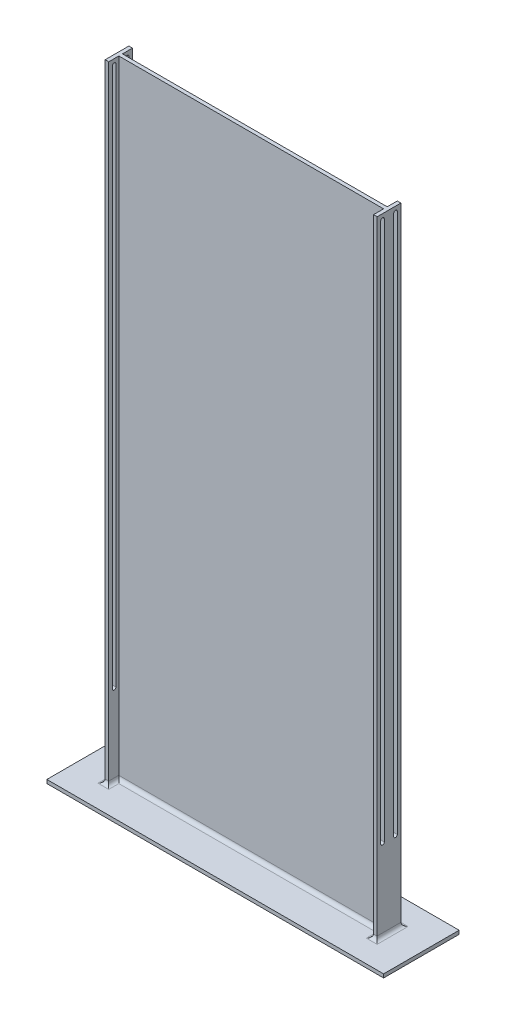
SolidWorks part; units mm, degrees
material "AISI 4340 Steel, annealed"
ref_plane "Front Plane" through (0, 0, 0) normal (0, 0, 1) x (1, 0, 0)
ref_plane "Top Plane" through (0, 0, 0) normal (0, 1, 0) x (1, 0, 0)
ref_plane "Right Plane" through (0, 0, 0) normal (1, 0, 0) x (0, 0, -1)
sketch "Sketch1" plane through (0, 0, 0) normal (1, 0, 0) x (0, 0, -1)
  line L0 (0, 0) -> (-100, 0)
  line L1 (-100, 0) -> (-100, -10)
  line L2 (-100, -10) -> (10, -10)
  line L3 (10, 0) -> (10, 1741.5)
  line L4 (10, 1741.5) -> (0, 1741.5)
  line L5 (0, 1741.5) -> (0, 0)
  line L6 (10, -10) -> (110, -10)
  line L7 (110, -10) -> (110, 0)
  line L8 (110, 0) -> (10, 0)
  dimension "D1" = 1751.5
  dimension "D2" = 10
  dimension "D3" = 10
  dimension "D4" = 100
extrude "Wall extrude" add sketch "Sketch1" along normal mid plane 736
sketch "Sketch2" plane through (368, 0, 0) normal (1, 0, 0) x (0, 0, -1)
  line L0 (5, 1741.5) -> (5, -10) construction
  line L1 (10, 1741.5) -> (0, 1741.5) construction
  line L2 (10, 0) -> (10, 1741.5) construction
  line L3 (-100, -10) -> (110, -10) construction
  line L4 (0, 1741.5) -> (38, 1741.5)
  line L6 (0, -10) -> (38, -10)
  line L7 (38, 1741.5) -> (38, -10)
  line L8 (18, 226.5) -> (18, 1726.5)
  line L9 (28, 1726.5) -> (28, 226.5)
  line L10 (-18, 1726.5) -> (-18, 226.5)
  line L11 (-8, 226.5) -> (-8, 1726.5)
  line L12 (0, 1741.5) -> (-28, 1741.5)
  line L13 (-28, 1741.5) -> (-28, -10)
  line L14 (-28, -10) -> (0, -10)
  line L15 (0, 1741.5) -> (0, 0) construction
  arc A0 (28, 1726.5) -> (18, 1726.5) centre (23, 1726.5) ccw
  arc A1 (18, 226.5) -> (28, 226.5) centre (23, 226.5) ccw
  arc A2 (-8, 226.5) -> (-18, 226.5) centre (-13, 226.5) cw
  arc A3 (-18, 1726.5) -> (-8, 1726.5) centre (-13, 1726.5) cw
  dimension "D1" = 10
  dimension "D5" = 10
  dimension "D2" = 13
  dimension "D3" = 15
  dimension "D4" = 15
  dimension "D6" = 13
  dimension "D7" = 236.5
  dimension "D8" = 5
  dimension "D9" = 28
extrude "Right guide extrude" add sketch "Sketch2" along normal blind 10
mirror "Left guide extrude" about plane through (0, 0, 0) normal (1, 0, 0) of "Right guide extrude"
sketch "Sketch3" plane through (0, -10, 0) normal (0, -1, 0) x (1, 0, 0)
  line L11 (368, 100) -> (-368, 100) construction
  line L12 (-468, 100) -> (468, 100)
  line L15 (-468, 100) -> (-468, -110)
  line L16 (-468, -110) -> (468, -110)
  line L17 (468, 100) -> (468, -110)
  line L18 (368, -110) -> (-368, -110) construction
  line L19 (-368, 100) -> (-368, 28) construction
  line L20 (368, 100) -> (368, 28) construction
  dimension "D2" = 100
  dimension "D1" = 100
extrude "Bottom foot completion" add sketch "Sketch3" against normal blind 10
sketch "Sketch4" plane through (0, 0, -10) normal (0, 0, -1) x (-1, 0, 0)
  line L0 (-368, 0) -> (-368, 1741.5) construction
  line L1 (-368, 136.5) -> (368, 136.5)
  line L2 (-368, 136.5) -> (-368, 126.5)
  line L3 (-368, 126.5) -> (368, 126.5)
  line L4 (368, 136.5) -> (368, 126.5)
  line L5 (368, 0) -> (368, 1741.5) construction
  line L6 (-368, -10) -> (368, -10) construction
  dimension "D1" = 146.5
  dimension "D2" = 10
extrude "Platform stopper" add sketch "Sketch4" along normal up to surface (28 mm away) up to face at (373, 870.75, -38)
fillet "Structural fillets" radius 10 15 edges at (-378, 0, -5) (378, 0, -5) (0, 0, 0) (-368, 126.5, -24) (368, 126.5, -24) (0, 126.5, -10) (368, 0, 14) (-368, 0, 14) (-373, 0, 28) (373, 0, 28) (-373, 0, -38) (-368, 0, -24) (368, 0, -24) (373, 0, -38) (0, 0, -10)
